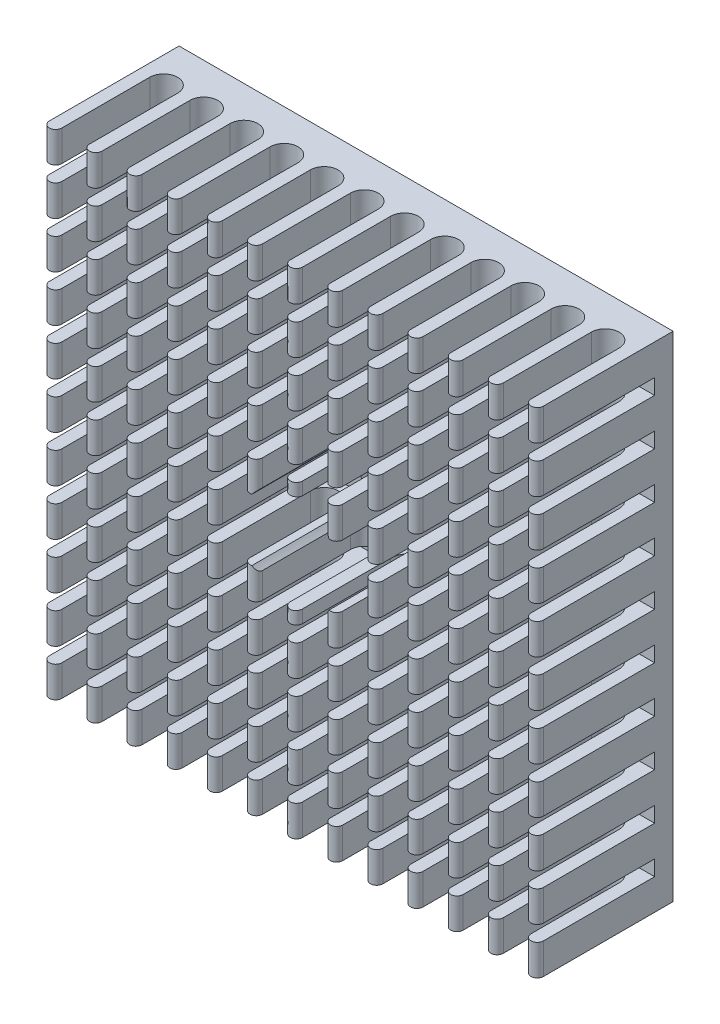
SolidWorks part; units mm, degrees
other "Camera1"
material "6061-T6 (SS)"
ref_plane "Front Plane" through (0, 0, 0) normal (0, 0, 1) x (1, 0, 0)
ref_plane "Top Plane" through (0, 0, 0) normal (0, 1, 0) x (1, 0, 0)
ref_plane "Right Plane" through (0, 0, 0) normal (1, 0, 0) x (0, 0, -1)
sketch "Sketch5" plane through (0, 0, 0) normal (0, 1, 0) x (1, 0, 0)
  line L0 (0, 0) -> (0, -4.1719) construction
  line L1 (20, 0) -> (-20, 0)
  line L2 (-20, 0) -> (-20, -10.5)
  line L3 (-19, -3.375) -> (-19, -10.5)
  line L4 (-16.75, -3.375) -> (-16.75, -10.5)
  line L5 (-15.75, -10.5) -> (-15.75, -3.375)
  line L6 (-13.5, -3.375) -> (-13.5, -10.5)
  line L7 (-12.5, -10.5) -> (-12.5, -3.375)
  line L8 (-10.25, -3.375) -> (-10.25, -10.5)
  line L9 (0.5, -10.5) -> (0.5, -3.375)
  line L10 (-9.25, -3.375) -> (-9.25, -10.5)
  line L11 (-7, -10.5) -> (-7, -3.375)
  line L12 (-6, -3.375) -> (-6, -10.5)
  line L13 (-3.75, -10.5) -> (-3.75, -3.375)
  line L14 (-2.75, -3.375) -> (-2.75, -10.5)
  line L15 (2.75, -3.375) -> (2.75, -10.5)
  line L16 (-0.5, -10.5) -> (-0.5, -3.375)
  line L17 (3.75, -10.5) -> (3.75, -3.375)
  line L18 (6, -3.375) -> (6, -10.5)
  line L19 (7, -10.5) -> (7, -3.375)
  line L20 (9.25, -3.375) -> (9.25, -10.5)
  line L21 (10.25, -3.375) -> (10.25, -10.5)
  line L22 (12.5, -10.5) -> (12.5, -3.375)
  line L23 (13.5, -3.375) -> (13.5, -10.5)
  line L24 (15.75, -10.5) -> (15.75, -3.375)
  line L25 (16.75, -3.375) -> (16.75, -10.5)
  line L26 (19, -3.375) -> (19, -10.5)
  line L27 (20, 0) -> (20, -10.5)
  arc A0 (-19, -3.375) -> (-16.75, -3.375) centre (-17.875, -3.375) cw
  arc A1 (-15.75, -3.375) -> (-13.5, -3.375) centre (-14.625, -3.375) cw
  arc A2 (-12.5, -3.375) -> (-10.25, -3.375) centre (-11.375, -3.375) cw
  arc A3 (-9.25, -3.375) -> (-7, -3.375) centre (-8.125, -3.375) cw
  arc A4 (-6, -3.375) -> (-3.75, -3.375) centre (-4.875, -3.375) cw
  arc A5 (-2.75, -3.375) -> (-0.5, -3.375) centre (-1.625, -3.375) cw
  arc A6 (-20, -10.5) -> (-19, -10.5) centre (-19.5, -10.5) ccw
  arc A7 (-16.75, -10.5) -> (-15.75, -10.5) centre (-16.25, -10.5) ccw
  arc A8 (-13.5, -10.5) -> (-12.5, -10.5) centre (-13, -10.5) ccw
  arc A9 (-10.25, -10.5) -> (-9.25, -10.5) centre (-9.75, -10.5) ccw
  arc A10 (-7, -10.5) -> (-6, -10.5) centre (-6.5, -10.5) ccw
  arc A11 (-3.75, -10.5) -> (-2.75, -10.5) centre (-3.25, -10.5) ccw
  arc A12 (-0.5, -10.5) -> (0.5, -10.5) centre (0, -10.5) ccw
  arc A13 (3.75, -10.5) -> (2.75, -10.5) centre (3.25, -10.5) cw
  arc A14 (7, -10.5) -> (6, -10.5) centre (6.5, -10.5) cw
  arc A15 (10.25, -10.5) -> (9.25, -10.5) centre (9.75, -10.5) cw
  arc A16 (13.5, -10.5) -> (12.5, -10.5) centre (13, -10.5) cw
  arc A17 (16.75, -10.5) -> (15.75, -10.5) centre (16.25, -10.5) cw
  arc A18 (20, -10.5) -> (19, -10.5) centre (19.5, -10.5) cw
  arc A19 (2.75, -3.375) -> (0.5, -3.375) centre (1.625, -3.375) ccw
  arc A20 (6, -3.375) -> (3.75, -3.375) centre (4.875, -3.375) ccw
  arc A21 (9.25, -3.375) -> (7, -3.375) centre (8.125, -3.375) ccw
  arc A22 (12.5, -3.375) -> (10.25, -3.375) centre (11.375, -3.375) ccw
  arc A23 (15.75, -3.375) -> (13.5, -3.375) centre (14.625, -3.375) ccw
  arc A24 (19, -3.375) -> (16.75, -3.375) centre (17.875, -3.375) ccw
  dimension "D1" = 1.125
  dimension "D2" = 0.5
  dimension "D3" = 3.375
  dimension "D4" = 10.5
extrude "Boss-Extrude2" add sketch "Sketch5" along normal mid plane 40
sketch "Sketch3" plane through (0, 0, 0) normal (1, 0, 0) x (0, 0, -1)
  line L1 (-12.5, 17.5) -> (-1.5, 17.5)
  line L2 (-12.5, 17.5) -> (-12.5, 16.25)
  line L3 (-12.5, 16.25) -> (-1.5, 16.25)
  line L4 (-1.5, 17.5) -> (-1.5, 16.25)
  line L7 (0, 0) -> (-16.0372, 0) construction
  line L8 (-12.5, 13.75) -> (-1.5, 13.75)
  line L9 (-12.5, 13.75) -> (-12.5, 12.5)
  line L10 (-12.5, 12.5) -> (-1.5, 12.5)
  line L11 (-1.5, 13.75) -> (-1.5, 12.5)
  line L12 (-12.5, 10) -> (-1.5, 10)
  line L13 (-12.5, 10) -> (-12.5, 8.75)
  line L14 (-12.5, 8.75) -> (-1.5, 8.75)
  line L15 (-1.5, 10) -> (-1.5, 8.75)
  line L16 (-12.5, 6.25) -> (-1.5, 6.25)
  line L17 (-12.5, 6.25) -> (-12.5, 5)
  line L18 (-12.5, 5) -> (-1.5, 5)
  line L19 (-1.5, 6.25) -> (-1.5, 5)
  line L20 (-12.5, 2.5) -> (-1.5, 2.5)
  line L21 (-12.5, 2.5) -> (-12.5, 1.25)
  line L22 (-12.5, 1.25) -> (-1.5, 1.25)
  line L23 (-1.5, 2.5) -> (-1.5, 1.25)
  line L24 (-1.5, -2.5) -> (-1.5, -1.25)
  line L25 (-12.5, -1.25) -> (-1.5, -1.25)
  line L26 (-12.5, -2.5) -> (-12.5, -1.25)
  line L27 (-12.5, -2.5) -> (-1.5, -2.5)
  line L28 (-1.5, -6.25) -> (-1.5, -5)
  line L29 (-12.5, -5) -> (-1.5, -5)
  line L30 (-12.5, -6.25) -> (-12.5, -5)
  line L31 (-12.5, -6.25) -> (-1.5, -6.25)
  line L32 (-1.5, -10) -> (-1.5, -8.75)
  line L33 (-12.5, -8.75) -> (-1.5, -8.75)
  line L34 (-12.5, -10) -> (-12.5, -8.75)
  line L35 (-12.5, -10) -> (-1.5, -10)
  line L36 (-1.5, -13.75) -> (-1.5, -12.5)
  line L37 (-12.5, -12.5) -> (-1.5, -12.5)
  line L38 (-12.5, -13.75) -> (-12.5, -12.5)
  line L39 (-12.5, -13.75) -> (-1.5, -13.75)
  line L40 (-1.5, -17.5) -> (-1.5, -16.25)
  line L41 (-12.5, -16.25) -> (-1.5, -16.25)
  line L42 (-12.5, -17.5) -> (-12.5, -16.25)
  line L43 (-12.5, -17.5) -> (-1.5, -17.5)
  dimension "D1" = 11
  dimension "D2" = 1.5
  dimension "D3" = 1.25
  dimension "D4" = 2.5
  dimension "D5" = 5
  dimension "D6" = 8.75
  dimension "D7" = 12.5
  dimension "D8" = 16.25
extrude "Cut-Extrude1" cut sketch "Sketch3" against normal through all both and the other way through all
sketch "Sketch6" plane through (0, 0, 0) normal (0, 0, -1) x (-1, 0, 0)
  circle A0 centre (0, 0) radius 4
  dimension "D1" = 8
extrude "Center Hole" cut sketch "Sketch6" against normal through all
